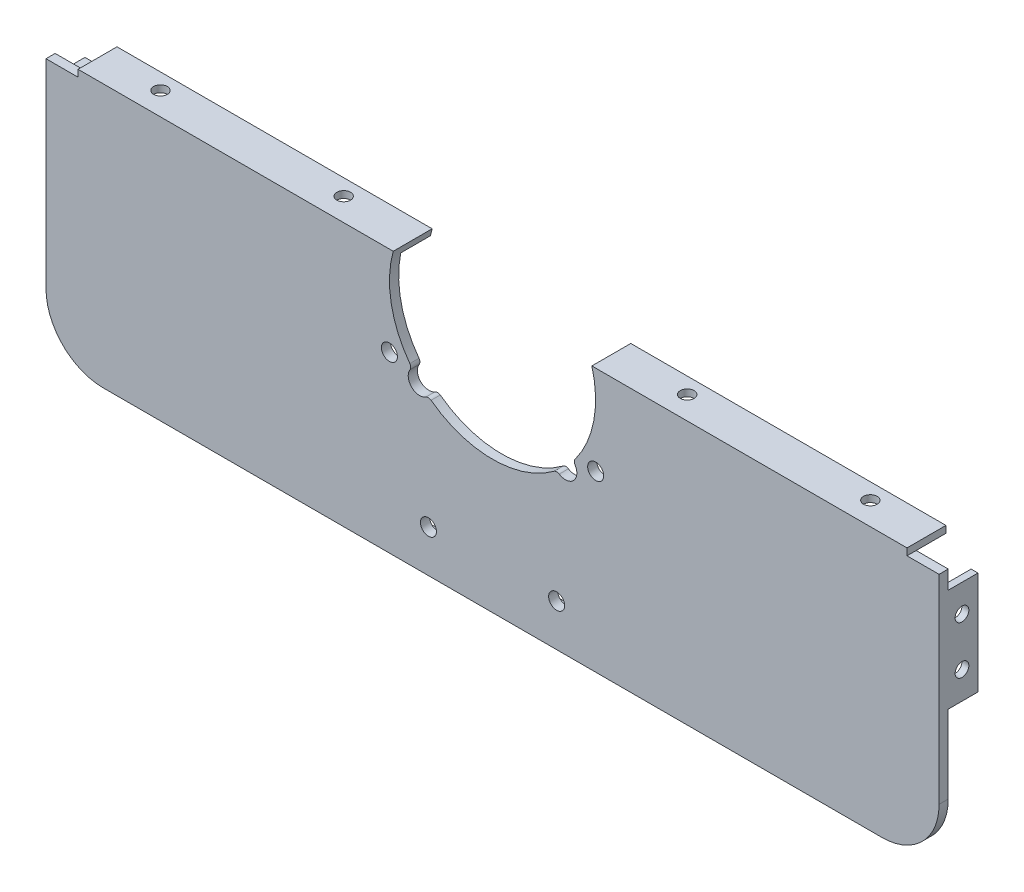
SolidWorks part; units mm, degrees
ref_plane "前视基准面" through (0, 0, 0) normal (0, 0, 1) x (1, 0, 0)
ref_plane "上视基准面" through (0, 0, 0) normal (0, 1, 0) x (1, 0, 0)
ref_plane "右视基准面" through (0, 0, 0) normal (1, 0, 0) x (0, 0, -1)
sketch "草图1" plane through (0, 0, 0) normal (0, 0, 1) x (1, 0, 0)
  line L0 (0, 0) -> (390, 0)
  line L1 (390, 0) -> (390, -90)
  line L2 (365, -115) -> (25, -115)
  line L3 (0, -90) -> (0, 0)
  arc A0 (390, -90) -> (365, -115) centre (365, -90) cw
  arc A1 (25, -115) -> (0, -90) centre (25, -90) cw
  dimension "D3" = 25
  dimension "D4" = 25
  dimension "D1" = 390
  dimension "D2" = 115
extrude "凸台-拉伸1" add sketch "草图1" along normal blind 4
sketch "草图5" plane through (0, 0, 0) normal (0, 1, 0) x (1, 0, 0)
  line L1 (0, -4) -> (390, -4)
  line L2 (0, -4) -> (0, 13)
  line L3 (0, 13) -> (390, 13)
  line L4 (390, -4) -> (390, 13)
  dimension "D1" = 17
extrude "凸台-拉伸2" add sketch "草图5" against normal blind 3
sketch "草图7" plane through (0, 0, 4) normal (0, 0, 1) x (1, 0, 0)
  line L0 (195, 69.8846) -> (195, -208.056) construction
  line L1 (195, -12) -> (156.6094, -50.3906) construction
  line L2 (390, 0) -> (0, 0) construction
  arc A0 (168.1477, -48.1103) -> (221.8523, -48.1103) centre (195, -12) ccw
  arc A1 (158.9692, -41.124) -> (165.876, -48.0308) centre (163.1802, -43.8198) ccw
  arc A2 (165.876, -48.0308) -> (168.1477, -48.1103) centre (166.9543, -49.7152) cw
  arc A3 (158.9692, -41.124) -> (158.8897, -38.8523) centre (157.2848, -40.0457) ccw
  circle A4 centre (195, -57) radius 48.5 construction
  circle A5 centre (167, -96.6011) radius 3.5
  circle A6 centre (149.9639, -39) radius 3.5
  circle A7 centre (223, -96.6011) radius 3.5
  circle A8 centre (240.0361, -39) radius 3.5
  arc A9 (231.0308, -41.124) -> (231.1103, -38.8523) centre (232.7152, -40.0457) cw
  arc A10 (224.124, -48.0308) -> (221.8523, -48.1103) centre (223.0457, -49.7152) ccw
  arc A11 (231.0308, -41.124) -> (224.124, -48.0308) centre (226.8198, -43.8198) cw
  arc A12 (231.1103, -38.8523) -> (158.8897, -38.8523) centre (195, -12) ccw
  point P4 (195, 0)
  dimension "D1" = 90
  dimension "D4" = 10
  dimension "D6" = 2
  dimension "D7" = 97
  dimension "D8" = 7
  dimension "D9" = 7
  dimension "D2" = 12
  dimension "D3" = 45
  dimension "D5" = 45
  dimension "D10" = 28
  dimension "D11" = 18
extrude "切除-拉伸1" cut sketch "草图7" against normal through all
sketch "草图8" plane through (0, 0, 0) normal (0, 0, -1) x (-1, 0, 0)
  line L1 (-365, -115) -> (-25, -115)
  line L2 (-365, -115) -> (-365, -112)
  line L3 (-365, -112) -> (-25, -112)
  line L4 (-25, -115) -> (-25, -112)
  dimension "D1" = 3
extrude "凸台-拉伸3" add sketch "草图8" along normal blind 13
sketch "草图9" plane through (0, 0, 0) normal (0, 1, 0) x (1, 0, 0)
  line L0 (390, 13) -> (238.3705, 13) construction
  line L1 (390, -4) -> (376, -4)
  line L2 (390, -4) -> (390, 13)
  line L3 (390, 13) -> (376, 13)
  line L4 (376, -4) -> (376, 13)
  line L5 (195, -22.3969) -> (195, 37.8683) construction
  line L6 (14, -4) -> (14, 13)
  line L7 (0, 13) -> (14, 13)
  line L8 (0, -4) -> (0, 13)
  line L9 (0, -4) -> (14, -4)
  dimension "D1" = 14
extrude "切除-拉伸2" cut sketch "草图9" against normal blind 3
sketch "草图18" plane through (0, 0, 0) normal (0, 0, -1) x (-1, 0, 0)
  line L0 (-390, -90) -> (-390, -3) construction
  line L1 (-390, -11) -> (-387, -11)
  line L2 (-390, -11) -> (-390, -56)
  line L3 (-390, -56) -> (-387, -56)
  line L4 (-387, -11) -> (-387, -56)
  line L5 (-390, -3) -> (-376, -3) construction
  line L6 (-195, -115) -> (-195, 20.0881) construction
  line L7 (-365, -115) -> (-25, -115) construction
  line L8 (-3, -11) -> (-3, -56)
  line L9 (0, -56) -> (-3, -56)
  line L10 (0, -11) -> (0, -56)
  line L11 (0, -11) -> (-3, -11)
  dimension "D1" = 3
  dimension "D2" = 45
  dimension "D3" = 8
extrude "凸台-拉伸4" add sketch "草图18" along normal blind 13
sketch "草图19" plane through (0, 0, 0) normal (0, 1, 0) x (1, 0, 0)
  line L0 (390, 13) -> (390, 0) construction
  line L1 (376, -4) -> (238.3705, -4) construction
  line L2 (195, -4) -> (195, 63.0767) construction
  line L3 (168.1477, -4) -> (221.8523, -4) construction
  circle A0 centre (270, 6) radius 3
  circle A1 centre (350, 6) radius 3
  circle A2 centre (40, 6) radius 3
  circle A3 centre (120, 6) radius 3
  dimension "D1" = 6
  dimension "D2" = 6
  dimension "D3" = 80
  dimension "D4" = 40
  dimension "D5" = 10
extrude "切除-拉伸3" cut sketch "草图19" against normal blind 13
sketch "草图20" plane through (390, 0, 0) normal (1, 0, 0) x (0, 0, -1)
  line L1 (13, -56) -> (0, -56) construction
  line L2 (-4, -90) -> (-4, -3) construction
  line L3 (13, -11) -> (13, -56) construction
  line L4 (13, -33.5) -> (-10.718, -33.5) construction
  circle A0 centre (6, -23) radius 3
  circle A1 centre (6, -44) radius 3
  dimension "D1" = 10
  dimension "D2" = 6
  dimension "D4" = 12
extrude "切除-拉伸4" cut sketch "草图20" against normal through all
sketch "草图22" plane through (0, -115, 0) normal (0, -1, 0) x (1, 0, 0)
  line L0 (195, 4) -> (195, -25.2352) construction
  line L1 (25, 4) -> (365, 4) construction
  line L2 (365, -13) -> (25, -13) construction
  circle A0 centre (75, -6) radius 3
  circle A1 centre (135, -6) radius 3
  circle A2 centre (315, -6) radius 3
  circle A3 centre (255, -6) radius 3
  point P12 (0, 0)
  point P15 (0, 0)
  dimension "D1" = 6
  dimension "D3" = 6
  dimension "D4" = 6
  dimension "D2" = 6
  dimension "D5" = 60
  dimension "D6" = 120
  dimension "D7" = 7
extrude "切除-拉伸5" cut sketch "草图22" against normal blind 13
